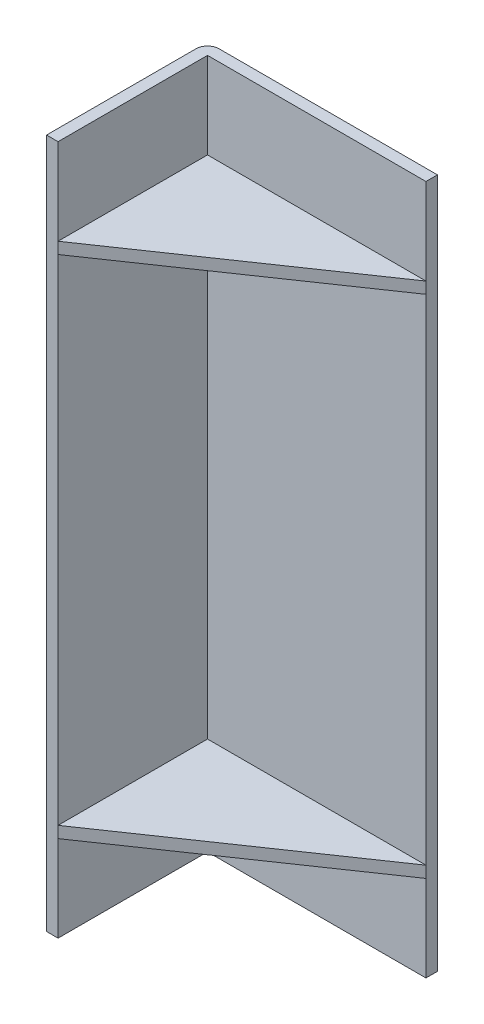
SolidWorks part; units mm, degrees
material "Fundición gris (SN)"
ref_plane "Alzado" through (0, 0, 0) normal (0, 0, 1) x (1, 0, 0)
ref_plane "Planta" through (0, 0, 0) normal (0, 1, 0) x (1, 0, 0)
ref_plane "Vista lateral" through (0, 0, 0) normal (1, 0, 0) x (0, 0, -1)
sketch "Croquis1" plane through (0, 0, 0) normal (0, 1, 0) x (1, 0, 0)
  line L0 (5, 0) -> (100, 0)
  line L1 (0, -5) -> (0, -70)
  line L2 (5, -5) -> (5, -70)
  line L3 (5, -5) -> (100, -5)
  line L4 (0, -70) -> (5, -70)
  line L5 (100, 0) -> (100, -5)
  arc A0 (5, 0) -> (0, -5) centre (5, -5) ccw
  arc A1 (5, -5) -> (5, -5) centre (5, -5) ccw
  point P6 (0, 0)
  dimension "D3" = 5
  dimension "D1" = 100
  dimension "D2" = 70
  dimension "D4" = 5
extrude "Saliente-Extruir1" add sketch "Croquis1" along normal mid plane 300
ref_plane "Plano1" through (0, 110, 0) normal (0, 1, 0) x (1, 0, 0)
sketch "Croquis2" plane through (0, 110, 0) normal (0, 1, 0) x (1, 0, 0)
  line L0 (100, -5) -> (5, -70)
rib "Nervio1" sketch "Croquis2" sketch "Croquis2" thickness 5 extrusion direction parallel to sketch draft on no parameters "D1"=5
mirror "Simetría1" about plane through (0, 0, 0) normal (0, 1, 0) of "Nervio1"
